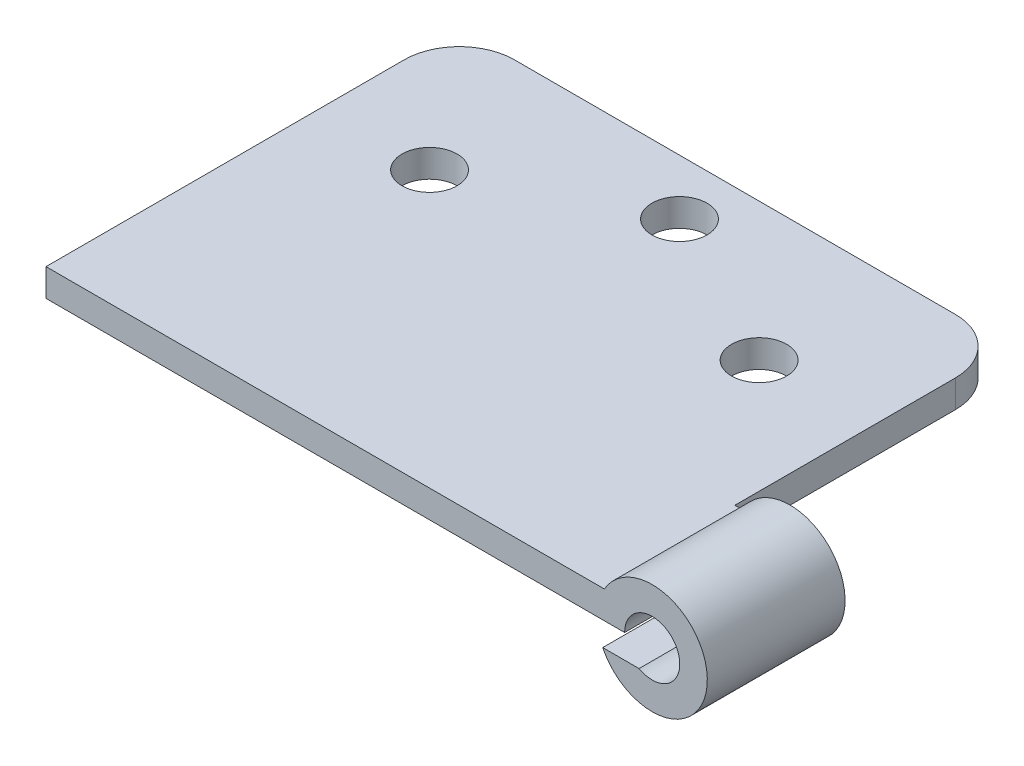
SolidWorks part; units mm, degrees
ref_plane "Front Plane" through (0, 0, 0) normal (0, 0, 1) x (1, 0, 0)
ref_plane "Top Plane" through (0, 0, 0) normal (0, 1, 0) x (1, 0, 0)
ref_plane "Right Plane" through (0, 0, 0) normal (1, 0, 0) x (0, 0, -1)
sketch "Sketch2" plane through (0, 0, 0) normal (0, 1, 0) x (1, 0, 0)
  line L1 (-100, -50) -> (100, -50)
  line L2 (-100, -50) -> (-100, 30)
  line L3 (-80, 50) -> (80, 50)
  line L4 (100, -50) -> (100, 30)
  line L5 (-100, -50) -> (100, 50) construction
  line L6 (-100, 50) -> (100, -50) construction
  circle A1 centre (58.794, 0) radius 10
  circle A2 centre (-60.804, 0) radius 10
  circle A3 centre (0, 29.8995) radius 10
  arc A4 (80, 50) -> (100, 30) centre (80, 30) cw
  arc A5 (-80, 50) -> (-100, 30) centre (-80, 30) ccw
  point P0 (0, 0)
  dimension "D3" = 20
  dimension "D4" = 20
  dimension "D5" = 20
  dimension "D6" = 20
  dimension "D1" = 200
  dimension "D2" = 100
extrude "Boss-Extrude2" add sketch "Sketch2" along normal blind 10 contours L2 L1 L4 A4 L3 A5 | A2 | A1 | A3
sketch "Sketch3" plane through (0, 0, 50) normal (0, 0, 1) x (1, 0, 0)
  line L0 (100, 10) -> (102.6333, 10)
  line L1 (100, 0) -> (110.0002, 0)
  line L6 (102.0352, -8.7101) -> (115.2323, -8.7101)
  line L13 (-100, 0) -> (100, 0)
  line L14 (100, 0) -> (100, 10)
  line L15 (100, 10) -> (-100, 10)
  line L16 (-100, 10) -> (-100, 0)
  line L17 (-100, 0) -> (100, 0)
  line L19 (100, 10) -> (-100, 10)
  line L20 (-100, 10) -> (-100, 0)
  arc A0 (102.0352, -8.7101) -> (102.6333, 10) centre (119.9998, 0.0802) ccw
  arc A1 (115.2323, -8.7101) -> (110.0002, 0) centre (119.9998, 0.0802) ccw
  dimension "D1" = 0
extrude "Boss-Extrude4" add sketch "Sketch3" along normal blind 50 contours L17 L1 A1 L6 A0 L0 L19 L20
